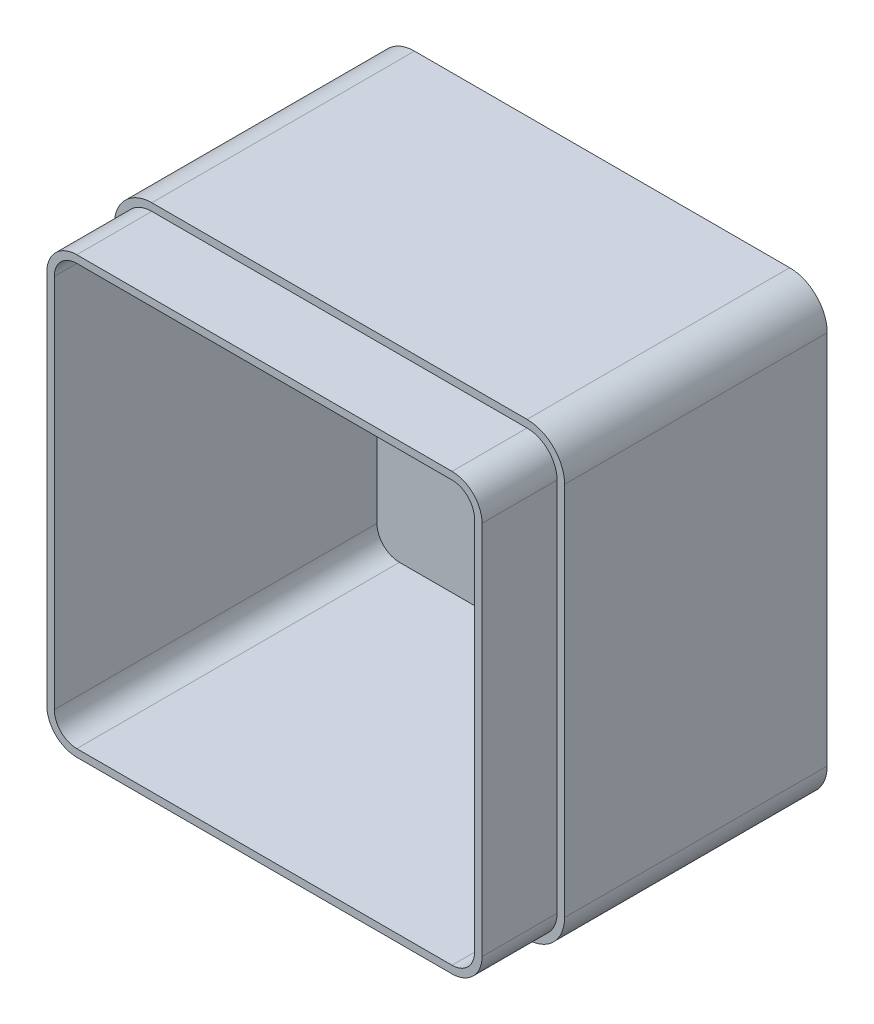
SolidWorks part; units mm, degrees
ref_plane "Front" through (0, 0, 0) normal (0, 0, 1) x (1, 0, 0)
ref_plane "Top" through (0, 0, 0) normal (0, 1, 0) x (1, 0, 0)
ref_plane "Right" through (0, 0, 0) normal (1, 0, 0) x (0, 0, -1)
sketch "Sketch1" plane through (0, 0, 0) normal (0, 0, 1) x (1, 0, 0)
  line L1 (0, 0) -> (120, 0)
  line L2 (0, 0) -> (0, 120)
  line L3 (0, 120) -> (120, 120)
  line L4 (120, 0) -> (120, 120)
  dimension "D1" = 120
  dimension "D2" = 120
extrude "Boss-Extrude1" add sketch "Sketch1" along normal blind 90
fillet "Fillet1" radius 10 4 edges at (0, 0, 45) (120, 0, 45) (120, 120, 45) (0, 120, 45)
shell "Shell1" thickness 4
sketch "Sketch3" plane through (0, 0, 90) normal (0, 0, 1) x (1, 0, 0)
  line L4 (0, 110) -> (0, 10)
  line L5 (10, 0) -> (110, 0)
  line L6 (120, 10) -> (120, 110)
  line L7 (110, 120) -> (10, 120)
  line L8 (0, 110) -> (0, 10)
  line L9 (10, 0) -> (110, 0)
  line L10 (120, 10) -> (120, 110)
  line L11 (110, 120) -> (10, 120)
  line L16 (2, 110) -> (2, 10)
  line L17 (10, 2) -> (110, 2)
  line L18 (118, 10) -> (118, 110)
  line L19 (110, 118) -> (10, 118)
  line L20 (2, 110) -> (2, 10)
  line L21 (10, 2) -> (110, 2)
  line L22 (118, 10) -> (118, 110)
  line L23 (110, 118) -> (10, 118)
  arc A4 (0, 10) -> (10, 0) centre (10, 10) ccw
  arc A5 (110, 0) -> (120, 10) centre (110, 10) ccw
  arc A6 (120, 110) -> (110, 120) centre (110, 110) ccw
  arc A7 (10, 120) -> (0, 110) centre (10, 110) ccw
  arc A8 (0, 10) -> (10, 0) centre (10, 10) ccw
  arc A9 (110, 0) -> (120, 10) centre (110, 10) ccw
  arc A10 (120, 110) -> (110, 120) centre (110, 110) ccw
  arc A11 (10, 120) -> (0, 110) centre (10, 110) ccw
  arc A16 (2, 10) -> (10, 2) centre (10, 10) ccw
  arc A17 (110, 2) -> (118, 10) centre (110, 10) ccw
  arc A18 (118, 110) -> (110, 118) centre (110, 110) ccw
  arc A19 (10, 118) -> (2, 110) centre (10, 110) ccw
  arc A20 (2, 10) -> (10, 2) centre (10, 10) ccw
  arc A21 (110, 2) -> (118, 10) centre (110, 10) ccw
  arc A22 (118, 110) -> (110, 118) centre (110, 110) ccw
  arc A23 (10, 118) -> (2, 110) centre (10, 110) ccw
  dimension "D1" = 0
  dimension "D2" = 2
extrude "Cut-Extrude1" cut sketch "Sketch3" against normal blind 20
